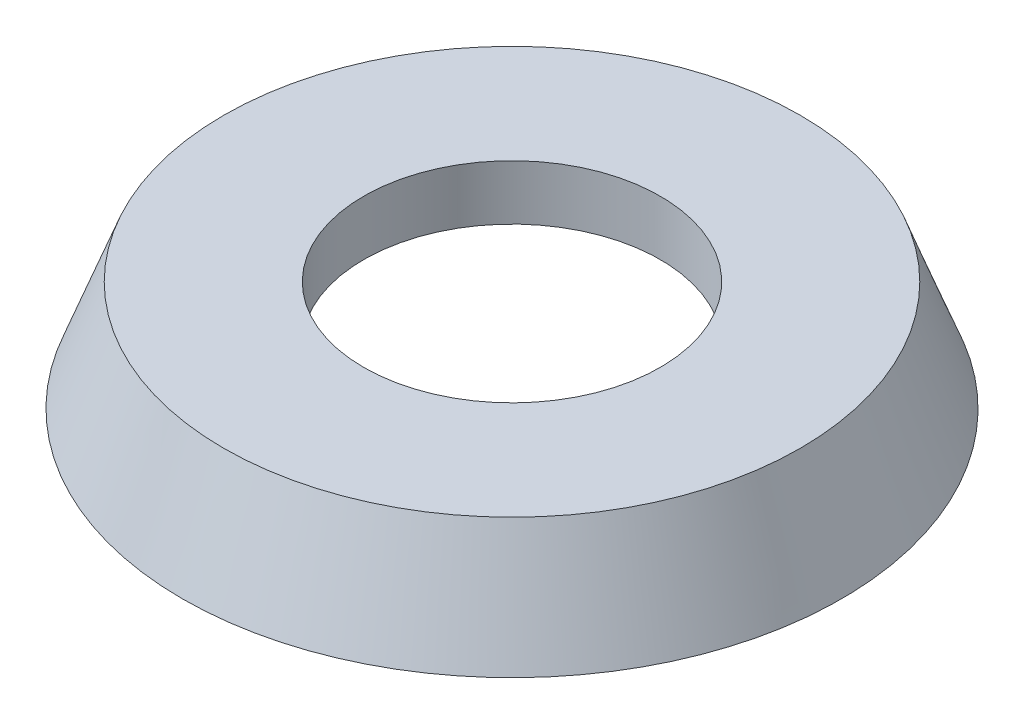
SolidWorks part; units mm, degrees
ref_plane "前视基准面" through (0, 0, 0) normal (0, 0, 1) x (1, 0, 0)
ref_plane "上视基准面" through (0, 0, 0) normal (0, 1, 0) x (1, 0, 0)
ref_plane "右视基准面" through (0, 0, 0) normal (1, 0, 0) x (0, 0, -1)
sketch "草图1" plane through (0, 0, 0) normal (0, 1, 0) x (1, 0, 0)
  circle A0 centre (0, 0) radius 12
  dimension "D1" = 24
ref_plane "基准面1" through (0, 4, 0) normal (0, 1, 0) x (1, 0, 0)
sketch "草图2" plane through (0, 4, 0) normal (0, 1, 0) x (1, 0, 0)
  circle A0 centre (0, 0) radius 10.5
  dimension "D1" = 21
loft "放样1" add profiles "草图1", "草图2"
sketch "草图3" plane through (0, 4, 0) normal (0, 1, 0) x (1, 0, 0)
  circle A0 centre (0, 0) radius 5.4
  dimension "D1" = 10.8
shell "抽壳2" thickness 2
extrude "切除-拉伸2" cut sketch "草图3" against normal through all contours A0
